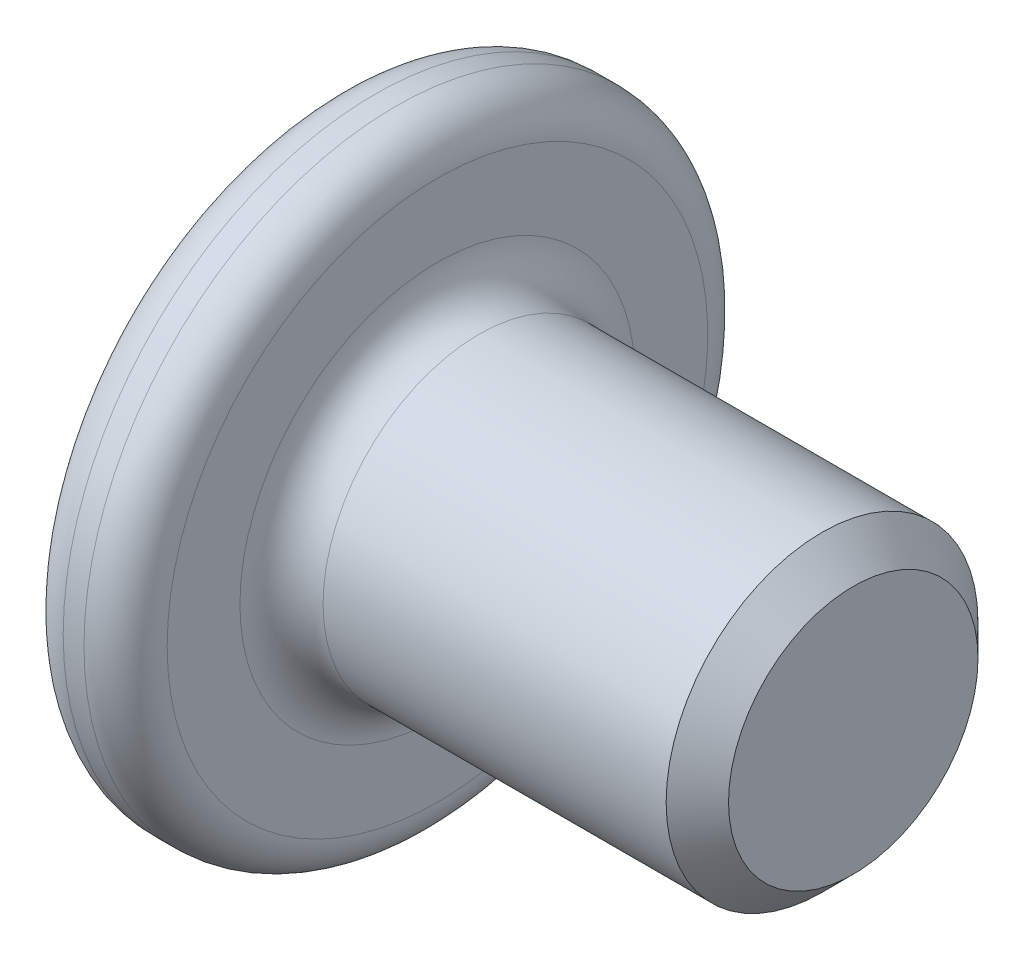
SolidWorks part; units mm, degrees
ref_plane "Спереди" through (0, 0, 0) normal (0, 0, 1) x (1, 0, 0)
ref_plane "Сверху" through (0, 0, 0) normal (0, 1, 0) x (1, 0, 0)
ref_plane "Справа" through (0, 0, 0) normal (1, 0, 0) x (0, 0, -1)
sketch "Эскиз1" plane through (0, 0, 0) normal (0, 0, 1) x (1, 0, 0)
  line L0 (-40.5884, 0) -> (1988.8334, 0) construction
  line L1 (0, 0) -> (0, 3)
  line L2 (0, 3) -> (1, 3)
  line L3 (1, 3) -> (1, 1.5)
  line L4 (1, 1.5) -> (5, 1.5)
  line L5 (5, 1.5) -> (5, 0)
  line L6 (0, 0) -> (5, 0)
  dimension "D1" = 4
  dimension "D2" = 1
  dimension "D3" = 3
  dimension "D4" = 6
revolve "Повернуть1" add sketch "Эскиз1" angle 360 about L0
fillet "Скругление1" radius 0.4 3 edges at (0, 0, 3) (1, 0, 3) (1, 0, 1.5)
sketch "Эскиз2" plane through (0, 0, 0) normal (-1, 0, 0) x (0, 0, 1)
  line L0 (-0.2, -0.2) -> (-0.2, -0.02) construction
  line L7 (0.2, -2) -> (-0.2, -2)
  line L8 (0.2, -2) -> (0.2, -0.2)
  line L9 (0.2, 2) -> (-0.2, 2)
  line L10 (-0.2, -2) -> (-0.2, -0.2)
  line L11 (0.2, -2) -> (-0.2, 2) construction
  line L12 (0.2, 2) -> (-0.2, -2) construction
  line L13 (-2, -0.2) -> (-0.2, -0.2)
  line L14 (-2, -0.2) -> (-2, 0.2)
  line L15 (-2, 0.2) -> (-0.2, 0.2)
  line L16 (2, -0.2) -> (2, 0.2)
  line L17 (-2, -0.2) -> (2, 0.2) construction
  line L18 (-2, 0.2) -> (2, -0.2) construction
  line L19 (-0.2, -0.02) -> (-0.2, 0.02)
  line L20 (0.2, -0.2) -> (0.2, -0.02) construction
  line L21 (0.2, -0.02) -> (0.2, 0.02)
  line L22 (0.2, 0.02) -> (0.2, 0.2) construction
  line L23 (0.2, 0.2) -> (0.2, 2)
  line L24 (-0.2, 0.02) -> (-0.2, 0.2) construction
  line L25 (-0.2, 0.2) -> (-0.2, 2)
  line L26 (-0.2, -0.2) -> (-0.02, -0.2) construction
  line L27 (-0.02, -0.2) -> (0.02, -0.2)
  line L28 (-0.2, 0.2) -> (-0.02, 0.2) construction
  line L29 (-0.02, 0.2) -> (0.02, 0.2)
  line L30 (0.02, 0.2) -> (0.2, 0.2) construction
  line L31 (0.2, 0.2) -> (2, 0.2)
  line L32 (0.02, -0.2) -> (0.2, -0.2) construction
  line L33 (0.2, -0.2) -> (2, -0.2)
  point P0 (0, 0)
  point P1 (0, 0)
  point P23 (0.2, 1.7527)
  dimension "D1" = 0.4
  dimension "D2" = 4
extrude "Вырез-Вытянуть1" cut sketch "Эскиз2" against normal blind 0.5
chamfer "Фаска1" distance 0.3 angle 45 1 edges at (5, 0, 1.5)
